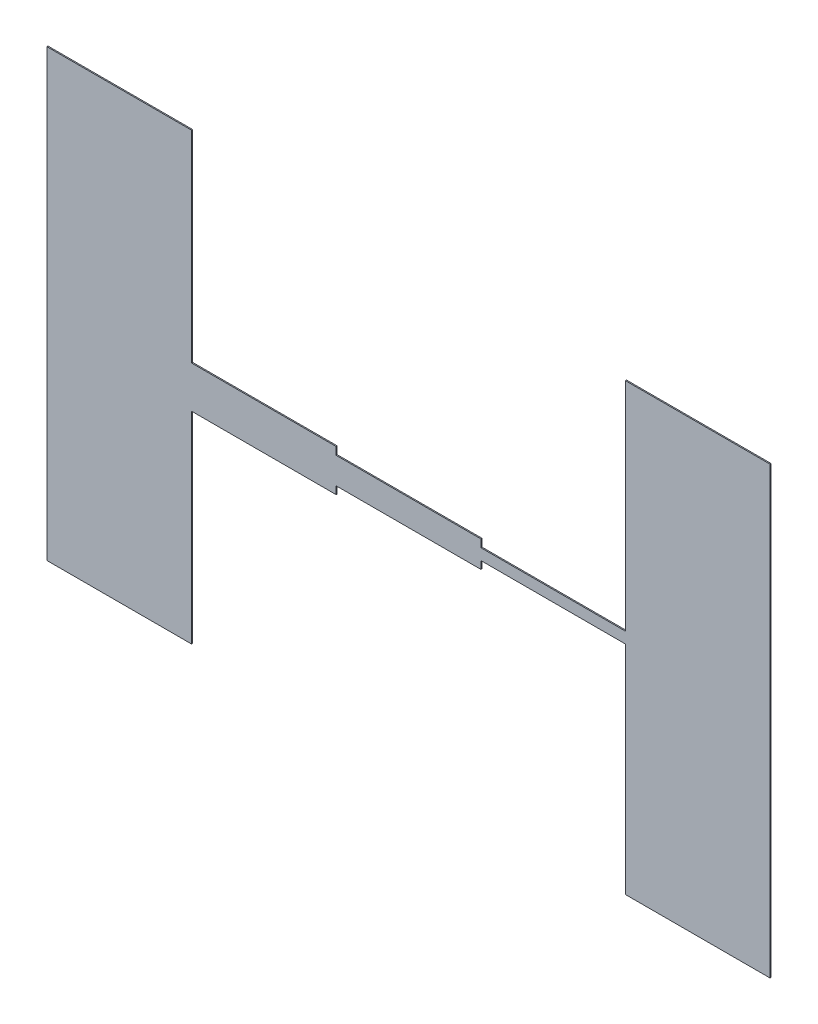
SolidWorks part; units mm, degrees
ref_plane "Front Plane" through (0, 0, 0) normal (0, 0, 1) x (1, 0, 0)
ref_plane "Top Plane" through (0, 0, 0) normal (0, 1, 0) x (1, 0, 0)
ref_plane "Right Plane" through (0, 0, 0) normal (1, 0, 0) x (0, 0, -1)
sketch "Sketch1" plane through (0, 0, 0) normal (0, 0, 1) x (1, 0, 0)
  line L0 (0, 0) -> (650, 0)
  line L1 (-650, -2000) -> (650, -2000)
  line L2 (-650, -2000) -> (-650, 2000)
  line L3 (-650, 2000) -> (650, 2000)
  line L4 (650, -2000) -> (650, -187.5)
  line L5 (-650, -2000) -> (650, 2000) construction
  line L6 (-650, 2000) -> (650, -2000) construction
  line L7 (650, 0) -> (7529.1767, 0) construction
  line L8 (650, 187.5) -> (650, 2000)
  line L9 (1950, -187.5) -> (650, -187.5)
  line L10 (1950, -187.5) -> (1950, -118.75)
  line L11 (1950, 187.5) -> (650, 187.5)
  line L13 (1950, -187.5) -> (650, 187.5) construction
  line L14 (1950, 187.5) -> (650, -187.5) construction
  line L15 (3250, -118.75) -> (1950, -118.75)
  line L16 (3250, -118.75) -> (3250, -50)
  line L17 (3250, 118.75) -> (1950, 118.75)
  line L19 (3250, -118.75) -> (1950, 118.75) construction
  line L20 (3250, 118.75) -> (1950, -118.75) construction
  line L21 (4550, -50) -> (3250, -50)
  line L23 (4550, 50) -> (3250, 50)
  line L25 (4550, -50) -> (3250, 50) construction
  line L26 (4550, 50) -> (3250, -50) construction
  line L27 (1950, 118.75) -> (1950, 187.5)
  line L28 (3250, 50) -> (3250, 118.75)
  line L29 (4550, 50) -> (4550, 2000)
  line L30 (5850, -2000) -> (4550, -2000)
  line L31 (5850, -2000) -> (5850, 2000)
  line L32 (5850, 2000) -> (4550, 2000)
  line L33 (4550, -2000) -> (4550, -50)
  line L34 (5850, -2000) -> (4550, 2000) construction
  line L35 (5850, 2000) -> (4550, -2000) construction
  point P0 (0, 0)
  point P9 (1300, 0)
  point P14 (2600, 0)
  point P19 (3900, 0)
  point P24 (5200, 0)
  dimension "D1" = 1300
  dimension "D2" = 4000
  dimension "D3" = 375
  dimension "D4" = 1300
  dimension "D5" = 1300
  dimension "D6" = 1300
  dimension "D7" = 100
  dimension "D8" = 237.5
  dimension "D9" = 1300
  dimension "D10" = 4000
extrude "Boss-Extrude1" add sketch "Sketch1" along normal blind 10
